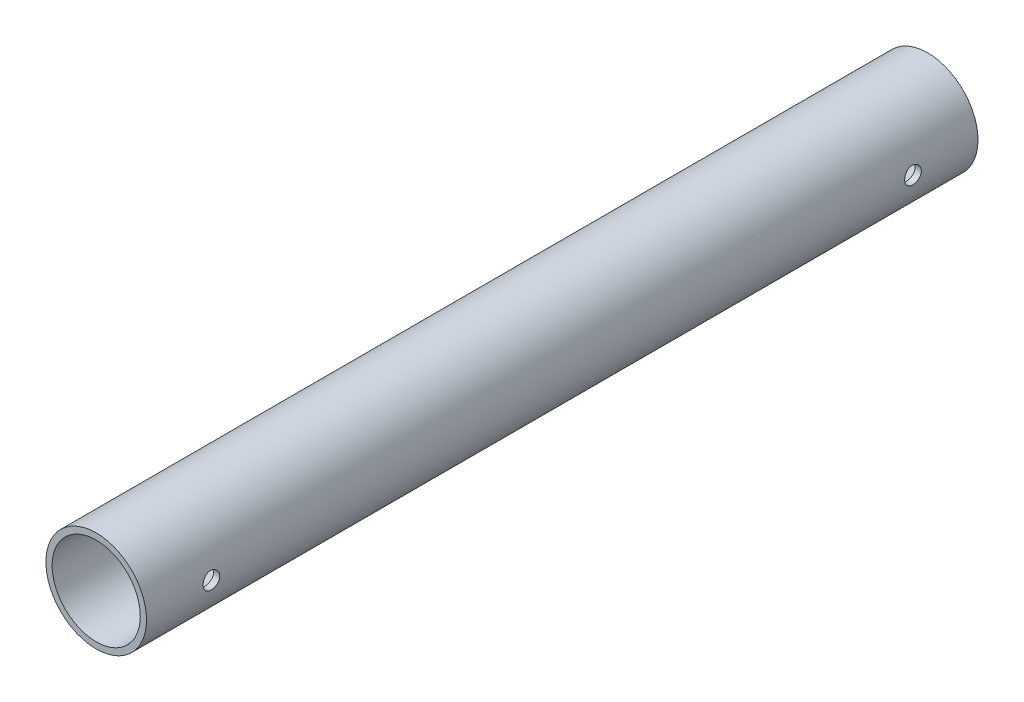
SolidWorks part; units mm, degrees
ref_plane "Front Plane" through (0, 0, 0) normal (0, 0, 1) x (1, 0, 0)
ref_plane "Top Plane" through (0, 0, 0) normal (0, 1, 0) x (1, 0, 0)
ref_plane "Right Plane" through (0, 0, 0) normal (1, 0, 0) x (0, 0, -1)
sketch "Sketch1" plane through (0, 0, 0) normal (0, 0, 1) x (1, 0, 0)
  circle A1 centre (0.713, 11.8211) radius 12.1
  circle A2 centre (0.713, 11.8211) radius 10.6
  dimension "D1" = 1.5
  dimension "D2" = 24.2
extrude "Boss-Extrude1" add sketch "Sketch1" along normal blind 100
sketch "Sketch8" plane through (0, 0, 0) normal (1, 0, 0) x (0, 0, -1)
  line L0 (-100, 23.9211) -> (-100, -0.2789) construction
  line L2 (-100, -0.2789) -> (0, -0.2789) construction
  line L3 (-118, 32.4865) -> (-118, -11.6901) construction
  circle A0 centre (-84.375, 12.2211) radius 2
  circle A1 centre (-151.625, 12.2211) radius 2
  dimension "D1" = 4
  dimension "D3" = 12.5
  dimension "D2" = 15.625
extrude "Cut-Extrude2" cut sketch "Sketch8" against normal through all both and the other way through all
mirror "Mirror1" about plane through (0.713, 11.8211, 0) normal (0, 0, 1) of "Cut-Extrude2", "Boss-Extrude1"
